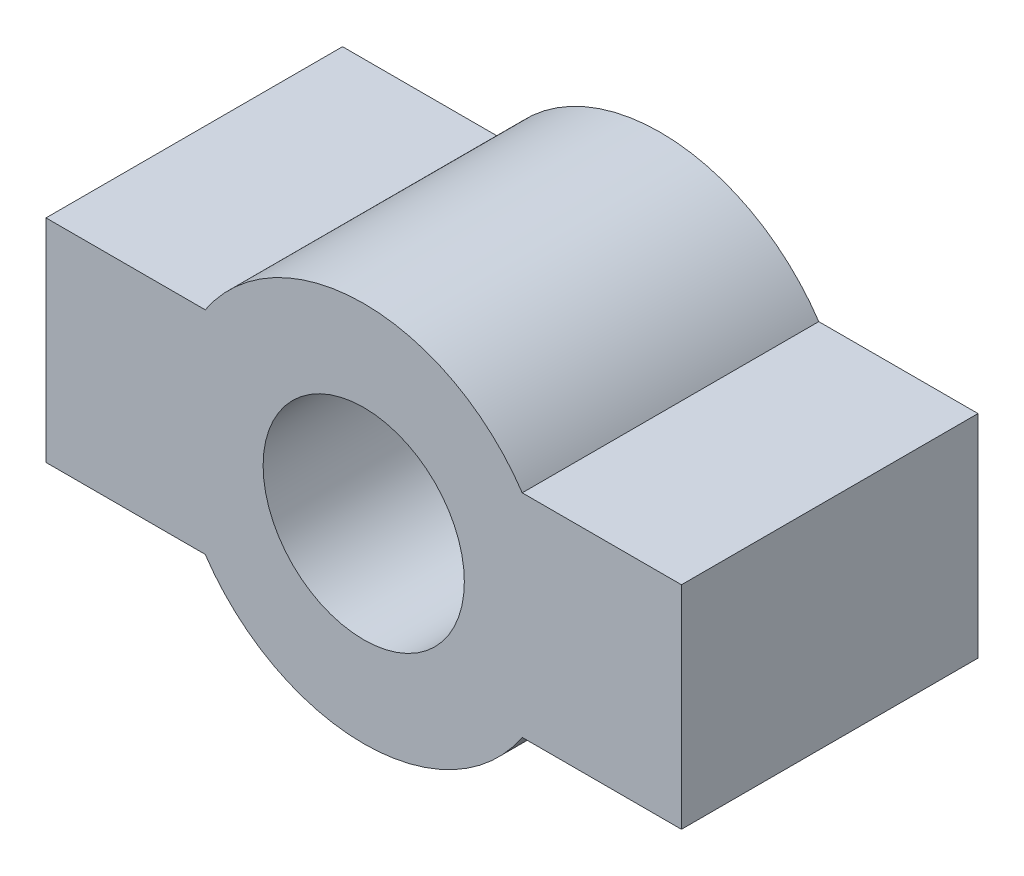
SolidWorks part; units mm, degrees
ref_plane "前视" through (0, 0, 0) normal (0, 0, 1) x (1, 0, 0)
ref_plane "上视" through (0, 0, 0) normal (0, 1, 0) x (1, 0, 0)
ref_plane "右视" through (0, 0, 0) normal (1, 0, 0) x (0, 0, -1)
sketch "草图1" plane through (0, 0, 0) normal (0, 0, 1) x (1, 0, 0)
  line L0 (14.9666, 10) -> (30, 10)
  line L1 (-30, 10) -> (-14.9666, 10)
  line L2 (-30, 10) -> (-30, -10)
  line L3 (-30, -10) -> (-14.9666, -10)
  line L4 (30, 10) -> (30, -10)
  line L5 (14.9666, -10) -> (30, -10)
  circle A0 centre (0, 0) radius 9.5
  arc A1 (-14.9666, -10) -> (14.9666, -10) centre (0, 0) ccw
  arc A2 (14.9666, 10) -> (-14.9666, 10) centre (0, 0) ccw
  dimension "D1" = 20
  dimension "D2" = 60
  dimension "D3" = 30
  dimension "D4" = 10
extrude "拉伸1" add sketch "草图1" along normal blind 28
